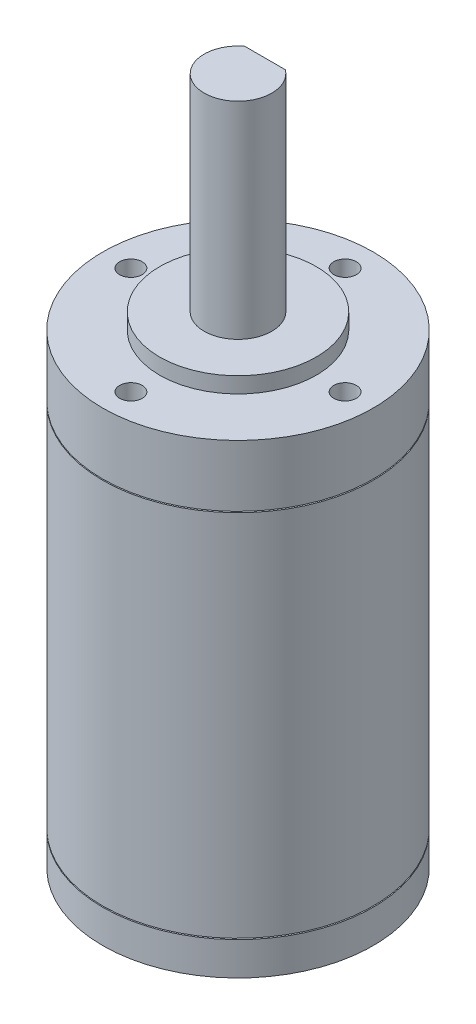
SolidWorks part; units mm, degrees
material "可锻铸铁"
ref_plane "前视" through (0, 0, 0) normal (0, 0, 1) x (1, 0, 0)
ref_plane "上视" through (0, 0, 0) normal (0, 1, 0) x (1, 0, 0)
ref_plane "右视" through (0, 0, 0) normal (1, 0, 0) x (0, 0, -1)
sketch "草图1" plane through (0, 0, 0) normal (0, 1, 0) x (1, 0, 0)
  circle A0 centre (0, 0) radius 12
  dimension "D1" = 24
extrude "凸台-拉伸1" add sketch "草图1" along normal blind 41.3
shell "抽壳6" thickness 2.1
sketch "草图2" plane through (0, 41.3, 0) normal (0, 1, 0) x (1, 0, 0)
  circle A0 centre (0, 0) radius 6.95
  dimension "D1" = 13.9
extrude "凸台-拉伸2" add sketch "草图2" along normal blind 1.4
sketch "草图3" plane through (0, 42.7, 0) normal (0, 1, 0) x (1, 0, 0)
  circle A0 centre (0, 0) radius 3
  dimension "D1" = 6
extrude "凸台-拉伸3" add sketch "草图3" along normal blind 18.3
sketch "草图4" plane through (0, 61, 0) normal (0, 1, 0) x (1, 0, 0)
  line L0 (-4.1804, 2.4) -> (5.155, 2.4)
  line L1 (5.155, 2.4) -> (-0.7181, 5.6828)
  line L2 (-0.7181, 5.6828) -> (-4.1804, 2.4)
  dimension "D1" = 2.4
extrude "切除-拉伸1" cut sketch "草图4" against normal blind 15
sketch "草图5" plane through (0, 0, 0) normal (0, -1, 0) x (1, 0, 0)
  circle A0 centre (0, 0) radius 3.1
  dimension "D1" = 6.2
extrude "切除-拉伸2" cut sketch "草图5" against normal blind 10
chamfer "倒角1" distance 0.9 angle 45 1 edges at (0, 0, -3.1)
sketch "草图7" plane through (0, 41.3, 0) normal (0, 1, 0) x (1, 0, 0)
  circle A0 centre (0, 9.5) radius 1
  dimension "D1" = 2
  dimension "D2" = 9.5
extrude "切除-拉伸3" cut sketch "草图7" against normal blind 10
pattern_circular "阵列(圆周)1" count 4 over 360 about axis through (0, 0, 0) along (0, 1, 0) of "切除-拉伸3"
sketch "草图8" plane through (0, 0, 0) normal (0, -1, 0) x (1, 0, 0)
  circle A0 centre (0, 8) radius 1.5
  dimension "D1" = 3
  dimension "D2" = 8
extrude "切除-拉伸4" cut sketch "草图8" against normal blind 10
pattern_circular "阵列(圆周)2" count 2 over 360 about axis through (0, 0, 0) along (0, 1, 0) of "切除-拉伸4"
sketch "草图10" plane through (0, 0, 0) normal (0, 0, 1) x (1, 0, 0)
  line L0 (-45.6772, 35.8) -> (29.4357, 35.8) construction
  line L1 (-39.0254, 3) -> (32.9484, 3) construction
  line L2 (10.5, 41.3) -> (8.5, 41.3) construction
  line L3 (-12, 0) -> (12, 0) construction
  line L4 (12, 0) -> (12, 41.3) construction
  line L5 (11.3902, 35.75) -> (12.3902, 35.75)
  line L6 (11.3902, 35.75) -> (11.3902, 35.85)
  line L7 (11.3902, 35.85) -> (12.3902, 35.85)
  line L8 (12.3902, 35.75) -> (12.3902, 35.85)
  line L9 (11.3902, 35.75) -> (12.3902, 35.85) construction
  line L10 (11.3902, 35.85) -> (12.3902, 35.75) construction
  line L11 (11.5, 2.95) -> (12.5, 2.95)
  line L12 (11.5, 2.95) -> (11.5, 3.05)
  line L13 (11.5, 3.05) -> (12.5, 3.05)
  line L14 (12.5, 2.95) -> (12.5, 3.05)
  line L15 (11.5, 2.95) -> (12.5, 3.05) construction
  line L16 (11.5, 3.05) -> (12.5, 2.95) construction
  line L17 (0, 62.1821) -> (0, -15.2994) construction
  point P8 (11.8902, 35.8)
  point P13 (12, 3)
  dimension "D1" = 5.5
  dimension "D2" = 3
  dimension "D3" = 1
  dimension "D4" = 1
  dimension "D5" = 0.1
  dimension "D6" = 0.1
revolve "切除-旋转1" cut sketch "草图10" angle 360 about L17
